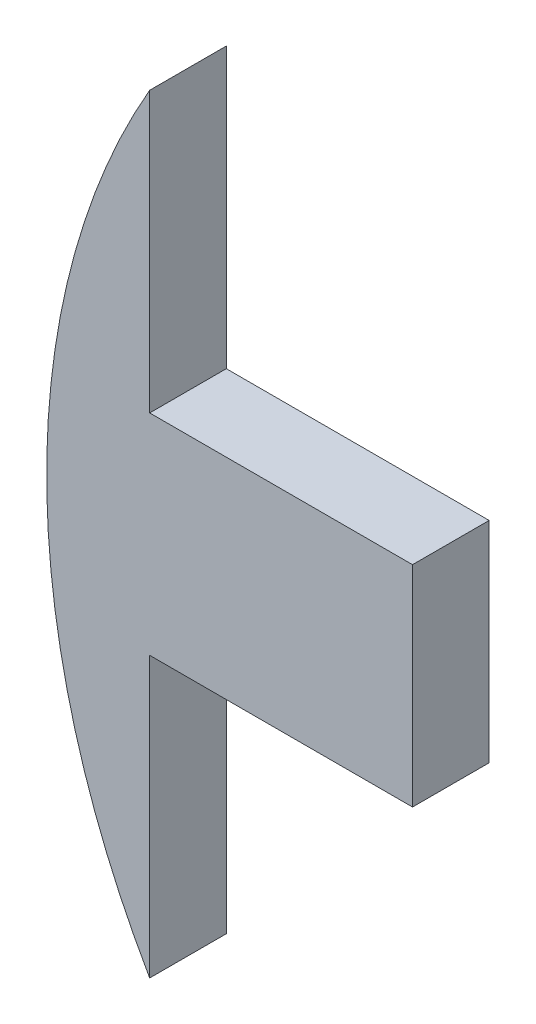
SolidWorks part; units mm, degrees
ref_plane "Front Plane" through (0, 0, 0) normal (0, 0, 1) x (1, 0, 0)
ref_plane "Top Plane" through (0, 0, 0) normal (0, 1, 0) x (1, 0, 0)
ref_plane "Right Plane" through (0, 0, 0) normal (1, 0, 0) x (0, 0, -1)
sketch "Sketch4" plane through (0, 0, 0) normal (0, 0, 1) x (1, 0, 0)
  line L43 (-10.5471, -11.2309) -> (-10.5471, -0.1809)
  line L44 (-10.5471, -0.1809) -> (-0.1547, -0.1809)
  line L45 (-10.5471, 8.1191) -> (-0.1547, 8.1191)
  line L46 (-10.5471, 19.1691) -> (-10.5471, 8.1191)
  line L47 (-0.1547, -0.1809) -> (-0.1547, 8.1191)
  arc A15 (-10.5471, 19.1691) -> (-10.5471, -11.2309) centre (15.7801, 3.9691) ccw
extrude "Boss-Extrude2" add sketch "Sketch4" along normal blind 3.03 contours L46 A15 L43 L44 L47 L45
